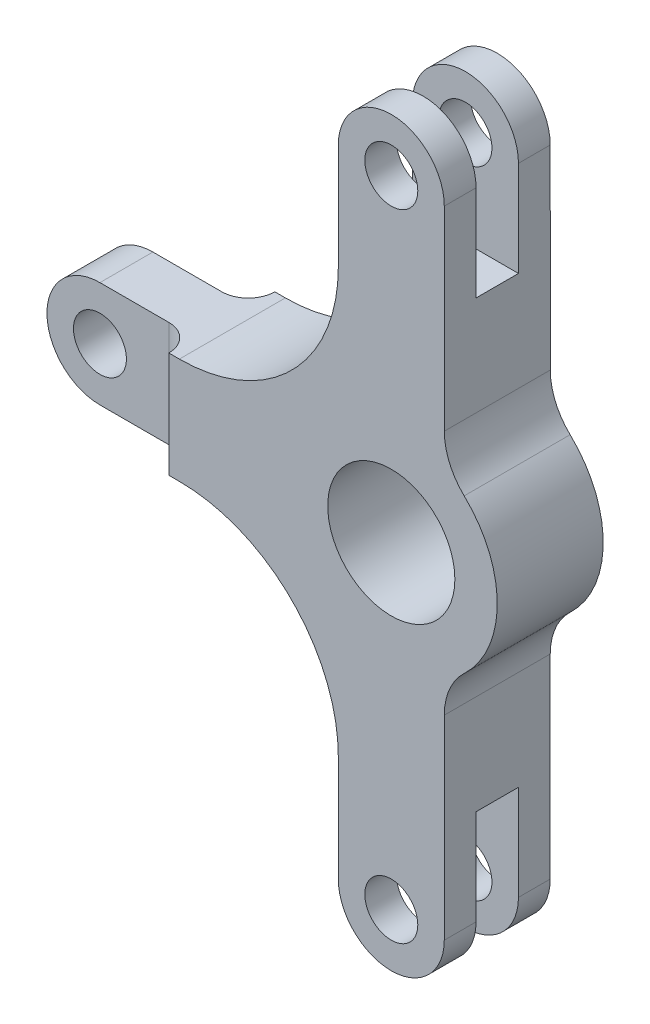
SolidWorks part; units mm, degrees
ref_plane "Front Plane" through (0, 0, 0) normal (0, 0, 1) x (1, 0, 0)
ref_plane "Top Plane" through (0, 0, 0) normal (0, 1, 0) x (1, 0, 0)
ref_plane "Right Plane" through (0, 0, 0) normal (1, 0, 0) x (0, 0, -1)
sketch "Sketch1" plane through (0, 0, 0) normal (0, 0, 1) x (1, 0, 0)
  line L0 (127, -294.7945) -> (127, -762)
  line L1 (0, 0) -> (0, -762) construction
  line L2 (127, 762) -> (127.1776, 294.8937)
  line L3 (-762, 127) -> (-508, 127)
  line L4 (-127, -508) -> (-127, -762)
  line L5 (-762, 0) -> (0, 0) construction
  line L6 (-127, 762) -> (-127, 508)
  line L8 (-508, -127) -> (-762, -127)
  circle A1 centre (0, 762) radius 63.5
  circle A2 centre (0, -762) radius 63.5
  circle A3 centre (-762, 0) radius 63.5
  arc A4 (-762, 127) -> (-762, -127) centre (-762, 0) ccw
  arc A6 (127, 762) -> (-127, 762) centre (0, 762) ccw
  arc A7 (174.6248, -184.451) -> (174.736, 184.3457) centre (0, 0) ccw
  arc A8 (127.1776, 294.8937) -> (174.736, 184.3457) centre (279.5776, 294.9531) ccw
  arc A9 (174.6248, -184.451) -> (127, -294.7945) centre (279.3996, -295.1217) ccw
  arc A10 (-127, -762) -> (127, -762) centre (0, -762) ccw
  arc A12 (-127, -508) -> (-508, -127) centre (-508, -508) ccw
  circle A13 centre (0, 0) radius 152.4
  arc A14 (-127, 508) -> (-508, 127) centre (-508, 508) cw
  dimension "D2" = 127
  dimension "D3" = 127
  dimension "D4" = 127
  dimension "D5" = 254
  dimension "D6" = 762
  dimension "D7" = 254
  dimension "D8" = 508
  dimension "D9" = 304.8
  dimension "D10" = 304.8
  dimension "D11" = 762
  dimension "D12" = 304.8
  dimension "D14" = 254
  dimension "D13" = 762
extrude "Boss-Extrude1" add sketch "Sketch1" along normal mid plane 254
sketch "Sketch2" plane through (0, 0, 0) normal (1, 0, 0) x (0, 0, -1)
  line L0 (0, 889) -> (0, 533.4) construction
  line L1 (127, 889) -> (-127, 889) construction
  line L2 (0, -889) -> (0, -533.4) construction
  line L3 (-127, -889) -> (127, -889) construction
  line L4 (-50.8, 889) -> (50.8, 889)
  line L5 (-50.8, -889) -> (50.8, -889)
  line L6 (-50.8, -889) -> (-50.8, -533.4)
  line L7 (-50.8, -533.4) -> (50.8, -533.4)
  line L8 (50.8, -533.4) -> (50.8, -889)
  line L9 (0, 533.4) -> (50.8, 533.4)
  line L10 (50.8, 533.4) -> (50.8, 889)
  line L11 (-50.8, 889) -> (-50.8, 533.4)
  line L12 (-50.8, 533.4) -> (0, 533.4)
  point P11 (0, 889)
  point P15 (0, -889)
  dimension "D1" = 355.6
  dimension "D2" = 355.6
  dimension "D3" = 50.8
  dimension "D4" = 50.8
extrude "Cut-Extrude1" cut sketch "Sketch2" against normal through all both and the other way through all
sketch "Sketch3" plane through (0, 127, 0) normal (0, 1, 0) x (1, 0, 0)
  line L0 (-889, 0) -> (-533.4, 0) construction
  line L1 (-889, 127) -> (-889, -127) construction
  line L2 (-533.4, -63.5) -> (-533.4, 63.5) construction
  line L3 (-889, 0) -> (-889, 63.5) construction
  line L4 (-889, 63.5) -> (-889, -63.5) construction
  line L5 (-889, -63.5) -> (-533.4, -63.5)
  line L6 (-533.4, -63.5) -> (-533.4, -178.3646)
  line L7 (-533.4, -178.3646) -> (-533.4, 247.0341)
  line L8 (-533.4, 247.0341) -> (-889, 247.0341)
  line L9 (-889, 247.0341) -> (-889, 63.5)
  line L10 (-889, 63.5) -> (-533.4, 63.5)
  line L11 (-889, -63.5) -> (-889, -178.3646)
  line L12 (-889, -178.3646) -> (-533.4, -178.3646)
  arc A0 (-533.4, -127) -> (-596.9, -63.5) centre (-596.9, -127) ccw
  arc A1 (-596.9, 63.5) -> (-533.4, 127) centre (-596.9, 127) ccw
  point P8 (-533.4, 0)
  line M8 (-508, 127) -> (-762, 127)
  line M9 (-762, 127) -> (-762, -127)
  line M10 (-762, -127) -> (-508, -127)
  dimension "D3" = 127
  dimension "D5" = 127
  dimension "D1" = 355.6
  dimension "D2" = 63.5
  dimension "D4" = 127
extrude "Cut-Extrude2" cut sketch "Sketch3" against normal blind 254 contours L10 A1 M8 M9 | L9 L10 L7 L8 M9 M8 | L11 L12 L6 L5 M10 M9 | A0 L5 M10 M9
